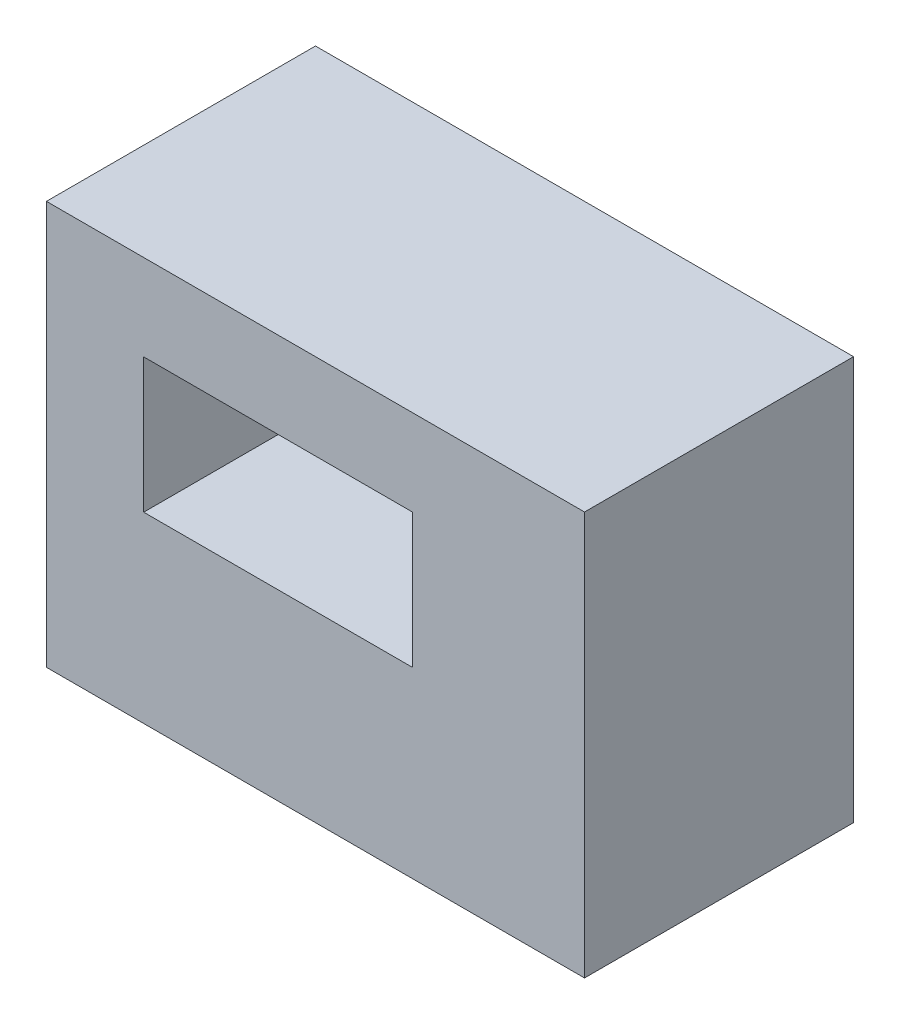
SolidWorks part; units mm, degrees
ref_plane "Front Plane" through (0, 0, 0) normal (0, 0, 1) x (1, 0, 0)
ref_plane "Top Plane" through (0, 0, 0) normal (0, 1, 0) x (1, 0, 0)
ref_plane "Right Plane" through (0, 0, 0) normal (1, 0, 0) x (0, 0, -1)
sketch "Sketch1" plane through (0, 0, 0) normal (0, 0, 1) x (1, 0, 0)
  line L1 (-68.5695, 39.9292) -> (33.0305, 39.9292)
  line L2 (-68.5695, 39.9292) -> (-68.5695, -36.2708)
  line L3 (-68.5695, -36.2708) -> (33.0305, -36.2708)
  line L4 (33.0305, 39.9292) -> (33.0305, -36.2708)
  point P4 (134.6305, -36.2708)
  dimension "D1" = 101.6
  dimension "D2" = 76.2
extrude "Boss-Extrude1" add sketch "Sketch1" along normal blind 50.8
sketch "Sketch2" plane through (0, 0, 50.8) normal (0, 0, 1) x (1, 0, 0)
  line L1 (-50.2061, 23.6799) -> (0.5939, 23.6799)
  line L2 (-50.2061, 23.6799) -> (-50.2061, -1.7201)
  line L3 (-50.2061, -1.7201) -> (0.5939, -1.7201)
  line L4 (0.5939, 23.6799) -> (0.5939, -1.7201)
  dimension "D1" = 50.8
  dimension "D2" = 25.4
extrude "Cut-Extrude1" cut sketch "Sketch2" against normal blind 25.4
equation "\"A\" = 4"
equation "\"B\" = 3"
equation "\"C\" = 2"
equation "\"D1@Sketch1\"=\"A\""
equation "\"D2@Sketch1\"=\"B\""
equation "\"D1@Boss-Extrude1\"=\"C\""
equation "\"D1@Sketch2\"=\"A\"-2"
equation "\"D2@Sketch2\"=\"D1@Sketch2\"/2"
